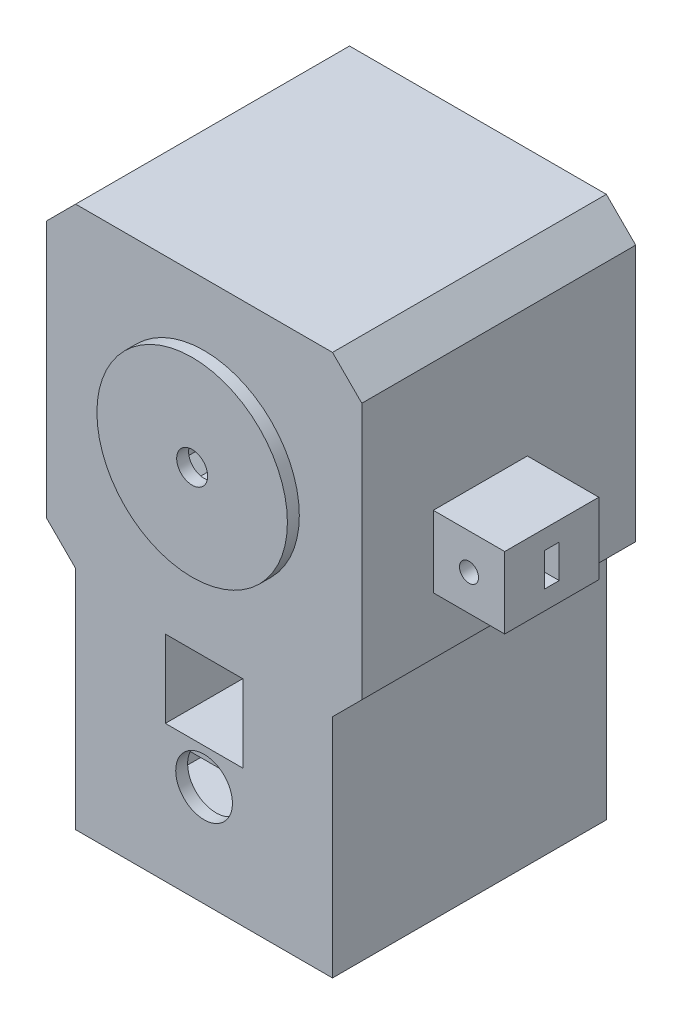
SolidWorks part; units mm, degrees
ref_plane "Alzado" through (0, 0, 0) normal (0, 0, 1) x (1, 0, 0)
ref_plane "Planta" through (0, 0, 0) normal (0, 1, 0) x (1, 0, 0)
ref_plane "Vista lateral" through (0, 0, 0) normal (1, 0, 0) x (0, 0, -1)
sketch "Croquis1" plane through (0, 0, 0) normal (0, 0, 1) x (1, 0, 0)
  line L0 (-19.5, -21.5) -> (-21.5, -19.5)
  line L1 (19.5, -21.5) -> (-19.5, -21.5)
  line L2 (21.5, -19.5) -> (21.5, 19.5)
  line L3 (19.5, 21.5) -> (-19.5, 21.5)
  line L4 (-21.5, -19.5) -> (-21.5, 19.5)
  line L5 (21.5, -21.5) -> (-21.5, 21.5) construction
  line L6 (21.5, 21.5) -> (-21.5, -21.5) construction
  line L7 (-19.5, 21.5) -> (-21.5, 19.5)
  line L8 (21.5, 19.5) -> (19.5, 21.5)
  line L9 (21.5, -19.5) -> (19.5, -21.5)
  line L10 (26.5, -21.5711) -> (26.5, 21.5711)
  line L11 (26.5, 21.5711) -> (21.5711, 26.5)
  line L12 (21.5711, 26.5) -> (-21.5711, 26.5)
  line L13 (-21.5711, 26.5) -> (-26.5, 21.5711)
  line L14 (-26.5, -21.5711) -> (-26.5, 21.5711)
  line L15 (-21.5711, -26.5) -> (-26.5, -21.5711)
  line L16 (21.5711, -26.5) -> (-21.5711, -26.5)
  line L17 (26.5, -21.5711) -> (21.5711, -26.5)
  point P0 (0, 0)
  dimension "D1" = 43
  dimension "D2" = 43
  dimension "D3" = 5
extrude "Saliente-Extruir1" add sketch "Croquis1" along normal mid plane 44
sketch "Croquis2" plane through (0, -26.5, 0) normal (0, -1, 0) x (1, 0, 0)
  line L4 (-21.5711, -22) -> (21.5711, -22)
  line L5 (21.5711, -22) -> (21.5711, 22)
  line L6 (21.5711, 22) -> (-21.5711, 22)
  line L7 (-21.5711, 22) -> (-21.5711, -22)
  line L8 (-21.5711, -22) -> (21.5711, -22)
  line L9 (21.5711, -22) -> (21.5711, 22)
  line L10 (21.5711, 22) -> (-21.5711, 22)
  line L11 (-21.5711, 22) -> (-21.5711, -22)
  dimension "D1" = 0
extrude "Saliente-Extruir2" add sketch "Croquis2" along normal blind 8
sketch "Croquis3" plane through (0, 0, 0) normal (0, 0, 1) x (1, 0, 0)
  line L0 (-19.5, -21.5) -> (19.5, -21.5) construction
  line L1 (-16.8806, -21.5) -> (16.8806, -21.5)
  line L2 (-16.8806, -21.5) -> (-16.8806, -29.5)
  line L3 (-16.8806, -29.5) -> (16.8806, -29.5)
  line L4 (16.8806, -21.5) -> (16.8806, -29.5)
  line L5 (0, 18.4155) -> (0, -35.026) construction
  dimension "D1" = 33.7612
  dimension "D2" = 8
extrude "Cortar-Extruir1" cut sketch "Croquis3" against normal through all contours L2 L1 L4 L3
sketch "Croquis4" plane through (0, 0, 22) normal (0, 0, -1) x (-1, 0, 0)
  line L10 (-26.5, -21.5711) -> (-21.5711, -26.5)
  line L11 (-21.5711, -26.5) -> (-21.5711, -34.5)
  line L12 (-21.5711, -34.5) -> (21.5711, -34.5)
  line L13 (21.5711, -34.5) -> (21.5711, -26.5)
  line L14 (21.5711, -26.5) -> (26.5, -21.5711)
  line L15 (26.5, -21.5711) -> (26.5, 21.5711)
  line L16 (26.5, 21.5711) -> (21.5711, 26.5)
  line L17 (21.5711, 26.5) -> (-21.5711, 26.5)
  line L18 (-21.5711, 26.5) -> (-26.5, 21.5711)
  line L19 (-26.5, 21.5711) -> (-26.5, -21.5711)
  line L20 (-26.5, -21.5711) -> (-21.5711, -26.5)
  line L21 (-21.5711, -26.5) -> (-21.5711, -34.5)
  line L22 (-21.5711, -34.5) -> (21.5711, -34.5)
  line L23 (21.5711, -34.5) -> (21.5711, -26.5)
  line L24 (21.5711, -26.5) -> (26.5, -21.5711)
  line L25 (26.5, -21.5711) -> (26.5, 21.5711)
  line L26 (26.5, 21.5711) -> (21.5711, 26.5)
  line L27 (21.5711, 26.5) -> (-21.5711, 26.5)
  line L28 (-21.5711, 26.5) -> (-26.5, 21.5711)
  line L29 (-26.5, 21.5711) -> (-26.5, -21.5711)
  circle A0 centre (0, 0) radius 11
  dimension "D2" = 22
  dimension "D1" = 0
extrude "Saliente-Extruir4" add sketch "Croquis4" against normal blind 2
sketch "Croquis7" plane through (0, 0, 24) normal (0, 0, 1) x (1, 0, 0)
  circle A0 centre (0, 0) radius 2.6
  circle A3 centre (0, 0) radius 16
  circle A4 centre (0, 0) radius 16
  dimension "D2" = 5.2
  dimension "D1" = 5
extrude "Saliente-Extruir5" add sketch "Croquis7" along normal blind 2
sketch "Croquis6" plane through (0, -29.5, 0) normal (0, 1, 0) x (1, 0, 0)
  line L0 (0, -24.5904) -> (0, 23.7869) construction
  line L1 (-14, 18) -> (14, 18)
  line L2 (-14, 18) -> (-14, 6)
  line L3 (-14, 6) -> (14, 6)
  line L4 (14, 18) -> (14, 6)
  dimension "D1" = 28
  dimension "D2" = 12
  dimension "D3" = 18
extrude "Cortar-Extruir3" cut sketch "Croquis6" against normal blind 13
sketch "Croquis8" plane through (0, 0, 0) normal (0, 0, 1) x (1, 0, 0)
  line L0 (-26.5, -21.5711) -> (-26.5, 21.5711)
  line L1 (-26.5, -21.5711) -> (-26.5, 21.5711)
  line L2 (-26.5, 21.5711) -> (-21.5711, 26.5)
  line L3 (-26.5, 21.5711) -> (-21.5711, 26.5)
  line L4 (-21.5711, 26.5) -> (21.5711, 26.5)
  line L5 (-21.5711, 26.5) -> (21.5711, 26.5)
  line L6 (21.5711, 26.5) -> (26.5, 21.5711)
  line L7 (21.5711, 26.5) -> (26.5, 21.5711)
  line L8 (26.5, 21.5711) -> (26.5, -21.5711)
  line L9 (26.5, 21.5711) -> (26.5, -21.5711)
  line L10 (26.5, -21.5711) -> (21.5711, -26.5)
  line L11 (26.5, -21.5711) -> (21.5711, -26.5)
  line L12 (21.5711, -26.5) -> (21.5711, -34.5)
  line L13 (21.5711, -26.5) -> (21.5711, -34.5)
  line L14 (21.5711, -34.5) -> (-21.5711, -34.5)
  line L15 (21.5711, -34.5) -> (-21.5711, -34.5)
  line L16 (-21.5711, -34.5) -> (-21.5711, -26.5)
  line L17 (-21.5711, -34.5) -> (-21.5711, -26.5)
  line L18 (-21.5711, -26.5) -> (-26.5, -21.5711)
  line L19 (-21.5711, -26.5) -> (-26.5, -21.5711)
  line L20 (0, 0) -> (-39.949, 0) construction
  line L21 (0, 0) -> (0, 31.7363) construction
  line L22 (26.5, -12) -> (38.5, -12)
  line L23 (-26.5, 0) -> (-38.5, 0)
  line L24 (-26.5, 0) -> (-26.5, -12)
  line L25 (-26.5, -12) -> (-38.5, -12)
  line L26 (-38.5, 0) -> (-38.5, -12)
  line L27 (38.5, 0) -> (38.5, -12)
  line L28 (26.5, 0) -> (38.5, 0)
  line L29 (26.5, 0) -> (26.5, -12)
  line L30 (-38.5, -12) -> (-26.5, 0) construction
  circle A0 centre (-32.5, -6) radius 1.6
  circle A1 centre (32.5, -6) radius 1.6
  dimension "D3" = 3.2
  dimension "D1" = 12
  dimension "D2" = 12
extrude "Saliente-Extruir6" add sketch "Croquis8" along normal blind 12 and the other way blind 3.8 contours L23 L26 L25 L1 | L28 L9 L22 L27
sketch "Croquis9" plane through (38.5, 0, 0) normal (1, 0, 0) x (0, 0, -1)
  line L0 (3.8, -6) -> (-12, -6) construction
  line L1 (3.8, 0) -> (3.8, -12) construction
  line L2 (-12, 0) -> (-12, -12) construction
  line L4 (-2.85, -3.2) -> (-5.35, -3.2)
  line L5 (-2.85, -3.2) -> (-2.85, -8.8)
  line L6 (-2.85, -8.8) -> (-5.35, -8.8)
  line L7 (-5.35, -3.2) -> (-5.35, -8.8)
  line L8 (-2.85, -3.2) -> (-5.35, -8.8) construction
  line L9 (-2.85, -8.8) -> (-5.35, -3.2) construction
  point P6 (-4.1, -6)
  dimension "D1" = 5.6
  dimension "D2" = 2.5
extrude "Cortar-Extruir4" cut sketch "Croquis9" against normal blind 10
mirror "Simetría1" about plane through (0, 0, 0) normal (1, 0, 0) of "Cortar-Extruir4"
sketch "Croquis11" plane through (0, -34.5, 0) normal (0, -1, 0) x (1, 0, 0)
  line L4 (-21.5711, 24) -> (-21.5711, -22)
  line L5 (-21.5711, -22) -> (21.5711, -22)
  line L6 (21.5711, -22) -> (21.5711, 24)
  line L7 (21.5711, 24) -> (-21.5711, 24)
  line L8 (-21.5711, 24) -> (-21.5711, -22)
  line L9 (-21.5711, -22) -> (21.5711, -22)
  line L10 (21.5711, -22) -> (21.5711, 24)
  line L11 (21.5711, 24) -> (-21.5711, 24)
  dimension "D1" = 0
extrude "Saliente-Extruir8" add sketch "Croquis11" along normal blind 30
sketch "Croquis12" plane through (0, 0, -22) normal (0, 0, -1) x (-1, 0, 0)
  line L0 (0, 0) -> (0, -75.996) construction
  line L1 (18.5711, -61.5) -> (-18.5711, -61.5)
  line L2 (18.5711, -61.5) -> (18.5711, -33.5)
  line L3 (18.5711, -33.5) -> (-18.5711, -33.5)
  line L4 (-18.5711, -61.5) -> (-18.5711, -33.5)
  line L5 (21.5711, -64.5) -> (21.5711, -26.5) construction
  line L6 (21.5711, -64.5) -> (-21.5711, -64.5) construction
  point P6 (-59.0322, -25.3426)
  dimension "D1" = 3
  dimension "D2" = 3
  dimension "D3" = 28
extrude "Cortar-Extruir5" cut sketch "Croquis12" against normal offset from surface (44 mm away) 2
sketch "Croquis14" plane through (0, 0, 24) normal (0, 0, 1) x (1, 0, 0)
  line L0 (0, 0) -> (0, -70.2297) construction
  line L1 (6.5, -28.5) -> (-6.5, -28.5)
  line L2 (6.5, -28.5) -> (6.5, -41.5)
  line L3 (6.5, -41.5) -> (-6.5, -41.5)
  line L4 (-6.5, -28.5) -> (-6.5, -41.5)
  line L5 (6.5, -28.5) -> (-6.5, -41.5) construction
  line L6 (6.5, -41.5) -> (-6.5, -28.5) construction
  point P0 (0, -35)
  point P7 (0, 0)
  point P8 (0, -6.9604)
  point P9 (0, 0)
  point P10 (6.3423, -35.3325)
  point P11 (0, 0)
  point P12 (-92.3947, -70.8967)
  point P13 (0, 0)
  point P14 (0, 0)
  point P15 (11.0356, -16.9331)
  point P16 (0, 0)
  point P18 (-6.3088, -41.3759)
  dimension "D1" = 35
  dimension "D2" = 13
  dimension "D3" = 13
extrude "Cortar-Extruir7" cut sketch "Croquis14" against normal blind 25
sketch "Croquis13" plane through (0, 0, 22) normal (0, 0, -1) x (-1, 0, 0)
  line L0 (18.5711, -47.5) -> (-18.5711, -47.5) construction
  line L1 (18.5711, -61.5) -> (18.5711, -33.5) construction
  line L2 (-18.5711, -33.5) -> (-18.5711, -61.5) construction
  circle A0 centre (0, -47.5) radius 4.7625
  dimension "D1" = 9.525
extrude "Cortar-Extruir6" cut sketch "Croquis13" against normal blind 2
sketch "Croquis15" plane through (0, 0, 22) normal (0, 0, -1) x (-1, 0, 0)
  line L0 (-6.5, -33.5) -> (-18.5711, -33.5)
  line L1 (-18.5711, -33.5) -> (-6.5711, -45.5)
  line L2 (-6.5711, -45.5) -> (6.5711, -45.5)
  line L3 (6.5711, -45.5) -> (18.5711, -33.5)
  line L4 (18.5711, -33.5) -> (6.5, -33.5)
  line L5 (6.5, -33.5) -> (6.5, -41.5)
  line L6 (6.5, -41.5) -> (-6.5, -41.5)
  line L7 (-6.5, -41.5) -> (-6.5, -33.5)
  dimension "D1" = 4
  dimension "D2" = 45
  dimension "D3" = 45
extrude "Saliente-Extruir9" add sketch "Croquis15" along normal blind 25
sketch "Croquis16" plane through (0, 0, -3) normal (0, 0, -1) x (-1, 0, 0)
  line L1 (-6.5, -41.5) -> (6.5, -41.5)
  line L2 (-6.5, -41.5) -> (-6.5, -28.5)
  line L3 (-6.5, -28.5) -> (6.5, -28.5)
  line L4 (6.5, -41.5) -> (6.5, -28.5)
extrude "Saliente-Extruir11" add sketch "Croquis16" against normal blind 3.2
